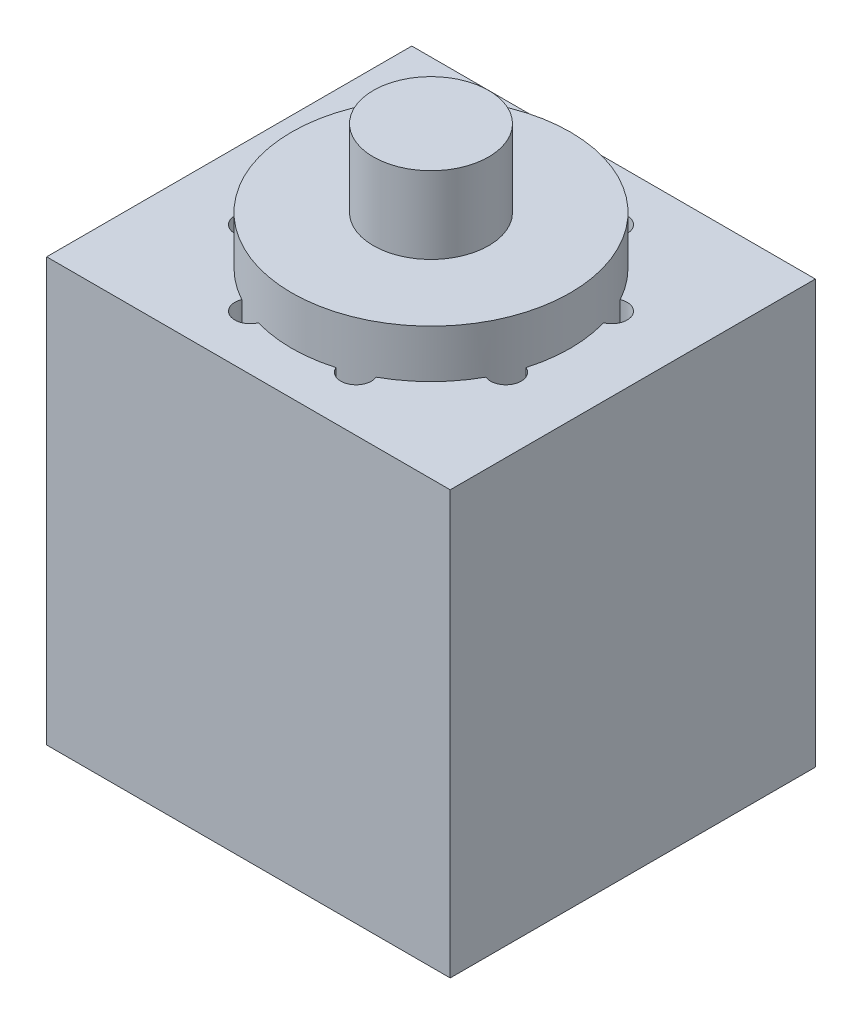
SolidWorks part; units mm, degrees
ref_plane "前视基准面" through (0, 0, 0) normal (0, 0, 1) x (1, 0, 0)
ref_plane "上视基准面" through (0, 0, 0) normal (0, 1, 0) x (1, 0, 0)
ref_plane "右视基准面" through (0, 0, 0) normal (1, 0, 0) x (0, 0, -1)
other "Configuration Table"
sketch "01_Housing_Profile" plane through (0, 0, 0) normal (0, 1, 0) x (1, 0, 0)
  line L1 (-105, -95) -> (105, -95)
  line L2 (-105, -95) -> (-105, 95)
  line L3 (-105, 95) -> (105, 95)
  line L4 (105, -95) -> (105, 95)
  line L5 (-105, -95) -> (105, 95) construction
  line L6 (-105, 95) -> (105, -95) construction
  circle A0 centre (66.5193, 27.5532) radius 8
  circle A1 centre (27.5532, 66.5193) radius 8
  circle A2 centre (-27.5532, 66.5193) radius 8
  circle A3 centre (-66.5193, 27.5532) radius 8
  circle A4 centre (-66.5193, -27.5532) radius 8
  circle A5 centre (-27.5532, -66.5193) radius 8
  circle A6 centre (27.5532, -66.5193) radius 8
  circle A7 centre (66.5193, -27.5532) radius 8
  point P0 (0, 0)
extrude "01_Housing_Block" add sketch "01_Housing_Profile" along normal blind 220
sketch "02_Face_Boss_Profile" plane through (0, 0, 0) normal (0, 1, 0) x (1, 0, 0)
  circle A0 centre (0, 0) radius 72.5
extrude "02_Face_Locating_Boss" add sketch "02_Face_Boss_Profile" along normal blind 245
sketch "03_Output_Shaft_Profile" plane through (0, 0, 0) normal (0, 1, 0) x (1, 0, 0)
  circle A0 centre (0, 0) radius 30
extrude "03_Output_Shaft" add sketch "03_Output_Shaft_Profile" along normal blind 285
